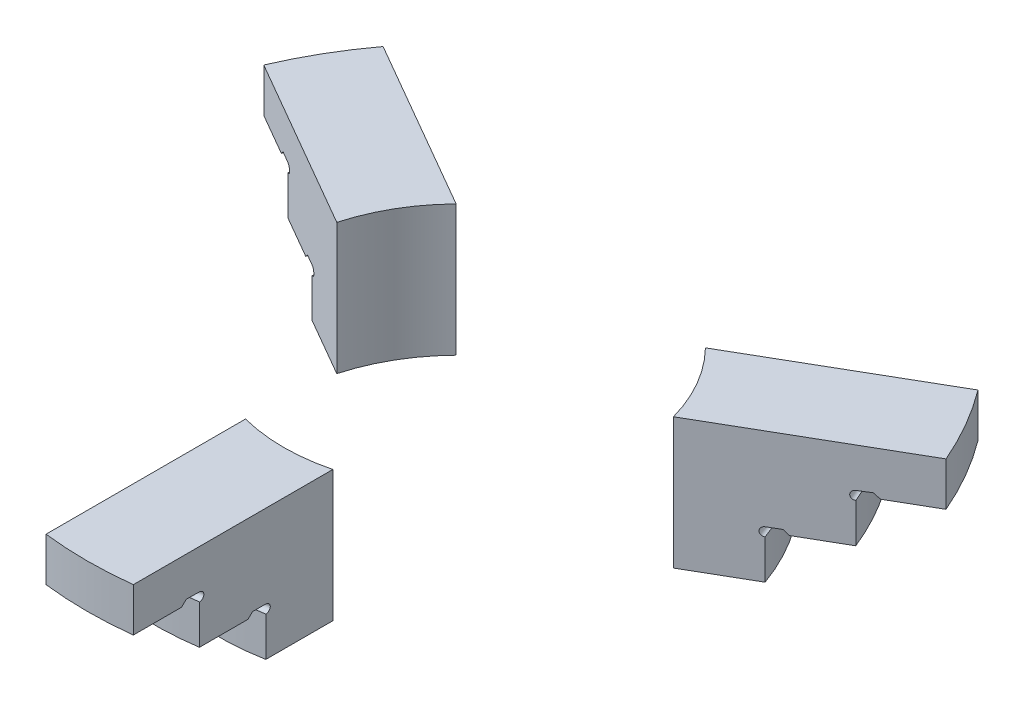
SolidWorks part; units mm, degrees
ref_plane "Front Plane" through (0, 0, 0) normal (0, 0, 1) x (1, 0, 0)
ref_plane "Top Plane" through (0, 0, 0) normal (0, 1, 0) x (1, 0, 0)
ref_plane "Right Plane" through (0, 0, 0) normal (1, 0, 0) x (0, 0, -1)
sketch "Sketch1" plane through (0, 0, 0) normal (0, 0, 1) x (1, 0, 0)
  line L0 (55, 0) -> (55, 9)
  line L1 (59.0144, 10) -> (70, 10)
  line L2 (40, 0) -> (55, 0)
  line L3 (70, 10) -> (70, 19)
  line L4 (74.0647, 20) -> (85, 20)
  line L5 (85, 20) -> (85, 30)
  line L6 (85, 30) -> (40, 30)
  line L7 (40, 30) -> (40, 0)
  line L8 (0, 0) -> (0, 27.372) construction
  line L9 (54.9964, 11) -> (57.9964, 11.0107)
  line L10 (57.9964, 11.0107) -> (59.0144, 10)
  line L11 (72.9843, 21.047) -> (69.9843, 20.9999)
  line L12 (74.0647, 20) -> (72.9843, 21.047)
  arc A0 (54.9964, 11) -> (55, 9) centre (55, 10) ccw
  arc A1 (69.9843, 20.9999) -> (70, 19) centre (70, 20) ccw
  dimension "D3" = 10
  dimension "D4" = 15
  dimension "D6" = 2
  dimension "D7" = 2
  dimension "D1" = 10
  dimension "D2" = 15
  dimension "D5" = 40
  dimension "D8" = 15
  dimension "D9" = 3
  dimension "D10" = 135
  dimension "D11" = 135
  dimension "D12" = 3
  dimension "D13" = 10
revolve "Revolve1" add sketch "Sketch1" angle 360 about L8
sketch "Sketch2" plane through (0, 0, 0) normal (0, 1, 0) x (1, 0, 0)
  line L0 (-81.6025, 58.6603) -> (0, 11.547)
  line L1 (-10, -100) -> (10, -100)
  line L2 (-10, -100) -> (-10, -5.7735)
  line L4 (10, -100) -> (10, -5.7735)
  line L5 (-81.6025, 58.6603) -> (-91.6025, 41.3397)
  line L6 (-91.6025, 41.3397) -> (-10, -5.7735)
  line L8 (91.6025, 41.3397) -> (10, -5.7735)
  line L9 (91.6025, 41.3397) -> (81.6025, 58.6603)
  line L10 (81.6025, 58.6603) -> (0, 11.547)
  line L12 (0, 0) -> (10, 0) [skipped]
  line L13 (5, 8.6603) -> (0, 0) [skipped]
  line L14 (0, 0) -> (-5, 8.6603) [skipped]
  dimension "D1" = 20
  dimension "D3" = 3
extrude "Cut-Extrude2" cut sketch "Sketch2" along normal through all flip side to cut
